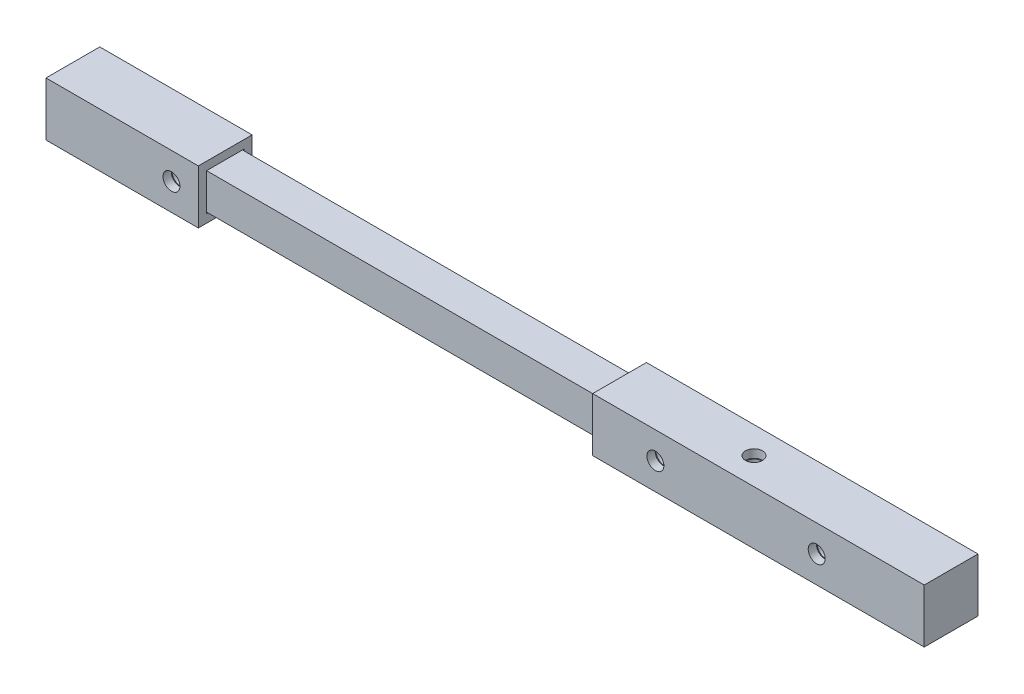
SolidWorks part; units mm, degrees
ref_plane "Front Plane" through (0, 0, 0) normal (0, 0, 1) x (1, 0, 0)
ref_plane "Top Plane" through (0, 0, 0) normal (0, 1, 0) x (1, 0, 0)
ref_plane "Right Plane" through (0, 0, 0) normal (1, 0, 0) x (0, 0, -1)
sketch "Sketch1" plane through (0, 0, 0) normal (1, 0, 0) x (0, 0, -1)
  line L1 (-3.175, -3.175) -> (3.175, -3.175)
  line L2 (-3.175, -3.175) -> (-3.175, 3.175)
  line L3 (-3.175, 3.175) -> (3.175, 3.175)
  line L4 (3.175, -3.175) -> (3.175, 3.175)
  line L5 (-3.175, -3.175) -> (3.175, 3.175) construction
  line L6 (-3.175, 3.175) -> (3.175, -3.175) construction
  point P0 (0, 0)
  dimension "D1" = 6.35
extrude "Boss-Extrude1" add sketch "Sketch1" along normal blind 152.4
sketch "Sketch2" plane through (0, 0, 3.175) normal (0, 0, 1) x (1, 0, 0)
  line L0 (0, 0) -> (20.6375, 0) construction
  line L1 (152.4, 0) -> (134.9375, 0) construction
  line L2 (152.4, 3.175) -> (152.4, -3.175) construction
  line L3 (134.9375, 0) -> (106.3625, 0) construction
  circle A0 centre (20.6375, 0) radius 1.5
  circle A1 centre (134.9375, 0) radius 1.5
  circle A2 centre (106.3625, 0) radius 1.5
  dimension "D2" = 3
  dimension "D1" = 20.6375
  dimension "D3" = 17.4625
  dimension "D4" = 28.575
extrude "Cut-Extrude1" cut sketch "Sketch2" against normal through all
sketch "Sketch3" plane through (0, 3.175, 0) normal (0, 1, 0) x (1, 0, 0)
  line L0 (104.8625, -3.175) -> (107.8625, -3.175) construction
  line L1 (104.8625, -3.175) -> (107.8625, -3.175) construction
  line L2 (106.3625, -3.175) -> (106.3625, 3.175) construction
  line L3 (152.4, 3.175) -> (0, 3.175) construction
  line L4 (106.3625, 0) -> (119.0625, 0) construction
  circle A0 centre (119.0625, 0) radius 1.5
  dimension "D2" = 3
  dimension "D1" = 12.7
extrude "Cut-Extrude2" cut sketch "Sketch3" against normal through all
sketch "Sketch4" plane through (152.4, 0, 0) normal (1, 0, 0) x (0, 0, -1)
  line L1 (4.7625, -4.7625) -> (-4.7625, -4.7625)
  line L2 (4.7625, -4.7625) -> (4.7625, 4.7625)
  line L3 (4.7625, 4.7625) -> (-4.7625, 4.7625)
  line L4 (-4.7625, -4.7625) -> (-4.7625, 4.7625)
  line L5 (4.7625, -4.7625) -> (-4.7625, 4.7625) construction
  line L6 (4.7625, 4.7625) -> (-4.7625, -4.7625) construction
  line L20 (3.302, -3.302) -> (3.302, 3.302)
  line L21 (-3.302, -3.302) -> (3.302, -3.302)
  line L22 (-3.302, 3.302) -> (-3.302, -3.302)
  line L23 (3.302, 3.302) -> (-3.302, 3.302)
  line L24 (3.302, -3.302) -> (3.302, 3.302)
  line L25 (-3.302, -3.302) -> (3.302, -3.302)
  line L26 (-3.302, 3.302) -> (-3.302, -3.302)
  line L27 (3.302, 3.302) -> (-3.302, 3.302)
  point P0 (0, 0)
  dimension "D1" = 9.525
  dimension "D2" = 0.127
extrude "Boss-Extrude2" add sketch "Sketch4" against normal blind 57.15 separate body
sketch "Sketch5" plane through (152.4, 0, 0) normal (1, 0, 0) x (0, 0, -1)
  line L4 (-4.7625, 4.7625) -> (-4.7625, -4.7625)
  line L5 (-4.7625, -4.7625) -> (4.7625, -4.7625)
  line L6 (4.7625, -4.7625) -> (4.7625, 4.7625)
  line L7 (4.7625, 4.7625) -> (-4.7625, 4.7625)
  line L8 (-4.7625, 4.7625) -> (-4.7625, -4.7625)
  line L9 (-4.7625, -4.7625) -> (4.7625, -4.7625)
  line L10 (4.7625, -4.7625) -> (4.7625, 4.7625)
  line L11 (4.7625, 4.7625) -> (-4.7625, 4.7625)
  dimension "D1" = 0
extrude "Boss-Extrude3" add sketch "Sketch5" along normal blind 1.5875
sketch "Sketch6" plane through (0, 0, 3.175) normal (0, 0, 1) x (1, 0, 0)
  circle A0 centre (134.9375, 0) radius 1.5 construction
  circle A1 centre (106.3625, 0) radius 1.5 construction
  circle A2 centre (134.9375, 0) radius 1.5
  circle A3 centre (106.3625, 0) radius 1.5
extrude "Cut-Extrude4" cut sketch "Sketch6" against normal through all both and the other way through all
sketch "Sketch7" plane through (0, 3.175, 0) normal (0, 1, 0) x (1, 0, 0)
  circle A0 centre (119.0625, 0) radius 1.5 construction
  circle A1 centre (119.0625, 0) radius 1.5
extrude "Cut-Extrude6" cut sketch "Sketch7" against normal through all both and the other way through all
sketch "Sketch8" plane through (0, 0, 0) normal (-1, 0, 0) x (0, 0, 1)
  line L0 (3.302, 3.302) -> (3.302, -3.302) construction
  line L1 (3.302, -3.302) -> (-3.302, -3.302) construction
  line L2 (-3.302, -3.302) -> (-3.302, 3.302) construction
  line L3 (-3.302, 3.302) -> (3.302, 3.302) construction
  line L4 (4.7625, -4.7625) -> (4.7625, 4.7625)
  line L5 (4.7625, 4.7625) -> (-4.7625, 4.7625)
  line L6 (-4.7625, 4.7625) -> (-4.7625, -4.7625)
  line L7 (-4.7625, -4.7625) -> (4.7625, -4.7625)
  line L8 (4.7625, -4.7625) -> (4.7625, 4.7625)
  line L9 (4.7625, 4.7625) -> (-4.7625, 4.7625)
  line L10 (-4.7625, 4.7625) -> (-4.7625, -4.7625)
  line L11 (-4.7625, -4.7625) -> (4.7625, -4.7625)
  line L12 (3.302, 3.302) -> (3.302, -3.302)
  line L13 (3.302, -3.302) -> (-3.302, -3.302)
  line L14 (-3.302, -3.302) -> (-3.302, 3.302)
  line L15 (-3.302, 3.302) -> (3.302, 3.302)
  dimension "D1" = 0
extrude "Boss-Extrude4" add sketch "Sketch8" against normal blind 25.4 separate body
sketch "Sketch9" plane through (0, 0, 0) normal (-1, 0, 0) x (0, 0, 1)
  line L4 (-4.7625, -4.7625) -> (4.7625, -4.7625)
  line L5 (4.7625, -4.7625) -> (4.7625, 4.7625)
  line L6 (4.7625, 4.7625) -> (-4.7625, 4.7625)
  line L7 (-4.7625, 4.7625) -> (-4.7625, -4.7625)
  line L8 (-4.7625, -4.7625) -> (4.7625, -4.7625)
  line L9 (4.7625, -4.7625) -> (4.7625, 4.7625)
  line L10 (4.7625, 4.7625) -> (-4.7625, 4.7625)
  line L11 (-4.7625, 4.7625) -> (-4.7625, -4.7625)
  dimension "D1" = 0
extrude "Boss-Extrude5" add sketch "Sketch9" along normal blind 1.5875
sketch "Sketch10" plane through (0, 0, 3.175) normal (0, 0, 1) x (1, 0, 0)
  circle A0 centre (20.6375, 0) radius 1.5 construction
  circle A1 centre (20.6375, 0) radius 1.5
extrude "Cut-Extrude8" cut sketch "Sketch10" against normal through all both and the other way through all
